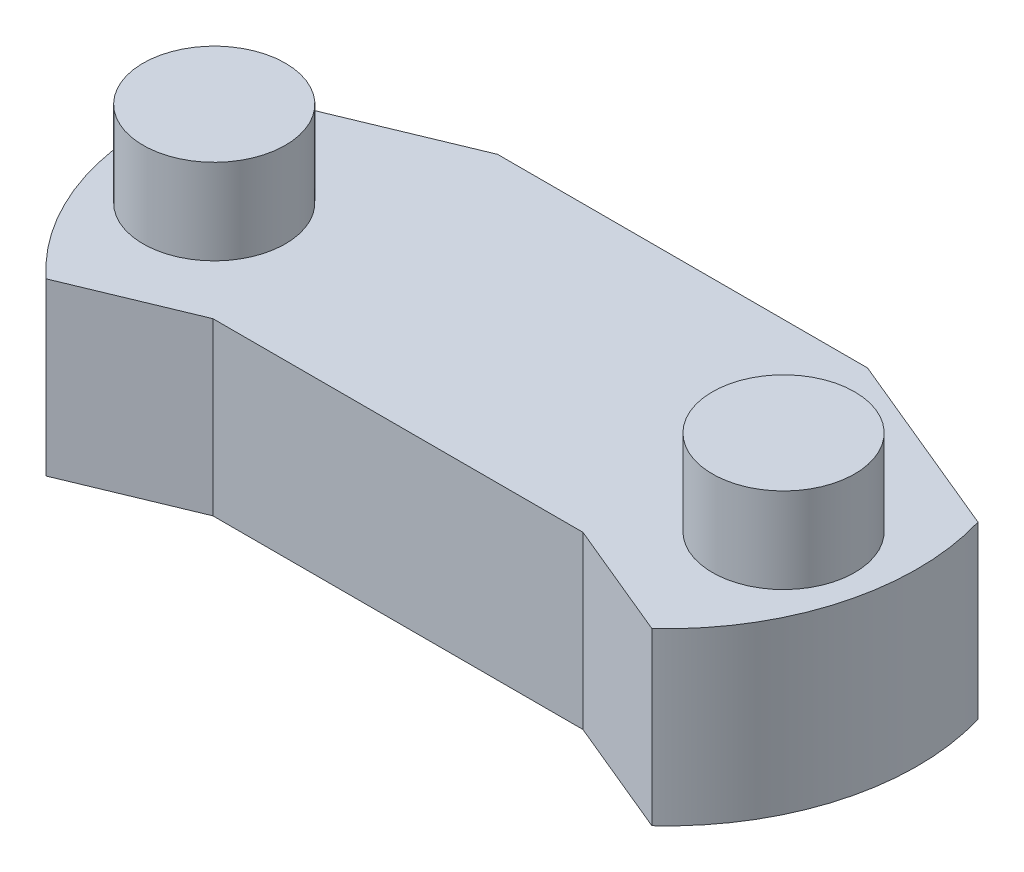
SolidWorks part; units mm, degrees
ref_plane "Front Plane" through (0, 0, 0) normal (0, 0, 1) x (1, 0, 0)
ref_plane "Top Plane" through (0, 0, 0) normal (0, 1, 0) x (1, 0, 0)
ref_plane "Right Plane" through (0, 0, 0) normal (1, 0, 0) x (0, 0, -1)
sketch "Sketch2" plane through (0, 0, 0) normal (0, 1, 0) x (1, 0, 0)
  line L0 (-21.487, 36.3493) -> (-21.487, -13.6507)
  line L3 (-21.487, -13.6507) -> (43.513, -13.6507)
  line L5 (-21.487, 36.3493) -> (-56.487, 21.8321)
  line L6 (-21.487, -13.6507) -> (-56.487, -28.1679)
  line L7 (-56.487, 21.8321) -> (-56.487, -28.1679)
  line L13 (43.513, -13.6507) -> (43.513, 36.3493)
  line L14 (-56.487, -28.1679) -> (-21.487, 36.3493)
  line L15 (-56.487, 21.8321) -> (-21.487, -13.6507)
  line L16 (-21.487, -13.6507) -> (-21.487, 36.3493)
  line L18 (-21.487, 36.3493) -> (43.513, 36.3493)
  line L19 (11.013, -53.9884) -> (11.013, 63.9884)
  line L20 (78.513, 21.8321) -> (43.513, -13.6507)
  line L21 (78.513, -28.1679) -> (43.513, 36.3493)
  line L22 (78.513, 21.8321) -> (78.513, -28.1679)
  line L23 (43.513, -13.6507) -> (78.513, -28.1679)
  line L24 (43.513, 36.3493) -> (78.513, 21.8321)
  line L25 (43.513, 36.3493) -> (43.513, -13.6507)
  circle A3 centre (-38.987, 4.0907) radius 12.5
  circle A4 centre (61.013, 4.0907) radius 12.5
  point P4 (11.013, 36.3493)
  point P9 (11.013, -13.6507)
  point P18 (11.013, 5)
  dimension "D4" = 35
  dimension "D3" = 50
  dimension "D1" = 25
  dimension "D2" = 50
extrude "Boss-Extrude1" add sketch "Sketch2" along normal blind 30 contours A3 L14 L5 L15 | A3 L15 L7 L14 | A3 L14 L6 L15 | A3 L15 L0 L14 | L3 L19 L18 L0 | L20 A4 L21 L13 | L21 A4 L20 L24 | L20 A4 L21 L22 | L21 A4 L20 L23 | L19 L3 L13 L18
fillet "Fillet1" radius 3 4 edges at (-56.487, 15, -21.8321) (-56.487, 15, 28.1679) (78.513, 15, -21.8321) (78.513, 15, 28.1679)
sketch "Sketch3" plane through (0, 0, 0) normal (0, -1, 0) x (-1, 0, 0)
  circle A1 centre (38.987, 4.0907) radius 12.5
  circle A2 centre (-61.013, 4.0907) radius 12.5
  dimension "D1" = 25
  dimension "D2" = 25
extrude "Boss-Extrude2" add sketch "Sketch3" against normal blind 45
sketch "Sketch4" plane through (0, 30, 0) normal (0, 1, 0) x (1, 0, 0)
  line L2 (-21.487, -13.6507) -> (-52.3376, -26.4468) construction
  line L7 (11.013, 36.3493) -> (11.013, -13.6507)
  line L8 (74.3636, -26.4468) -> (64.2102, -22.2354)
  line L9 (-52.3376, -26.4468) -> (-21.487, -13.6507)
  line L10 (-56.487, 19.8286) -> (-56.487, -23.6757)
  line L11 (-52.3376, -26.4468) -> (-42.1841, -22.2354)
  line L12 (-56.487, 19.8286) -> (-56.487, -23.6757)
  line L13 (78.513, 19.8286) -> (78.513, -23.6757)
  arc A0 (-54.6364, 22.5997) -> (-42.1841, -22.2354) centre (-12.5033, 10.1548) ccw
  arc A8 (78.513, -23.6757) -> (74.3636, -26.4468) centre (75.513, -23.6757) cw
  arc A9 (76.6624, 22.5997) -> (78.513, 19.8286) centre (75.513, 19.8286) cw
  arc A10 (-56.487, -23.6757) -> (-52.3376, -26.4468) centre (-53.487, -23.6757) ccw
  arc A11 (-54.6364, 22.5997) -> (-56.487, 19.8286) centre (-53.487, 19.8286) ccw
  arc A12 (-56.487, -23.6757) -> (-52.3376, -26.4468) centre (-53.487, -23.6757) ccw
  arc A13 (-54.6364, 22.5997) -> (-56.487, 19.8286) centre (-53.487, 19.8286) ccw
  arc A14 (76.6624, 22.5997) -> (64.2102, -22.2354) centre (34.5293, 10.1548) cw
  arc M9 (-54.6364, 22.5997) -> (-56.487, 19.8286) centre (-53.487, 19.8286) ccw
  line M10 (-56.487, 19.8286) -> (-56.487, -23.6757)
  arc M11 (-56.487, -23.6757) -> (-52.3376, -26.4468) centre (-53.487, -23.6757) ccw
  line M12 (-52.3376, -26.4468) -> (-21.487, -13.6507)
  line M14 (43.513, -13.6507) -> (74.3636, -26.4468)
  arc M15 (74.3636, -26.4468) -> (78.513, -23.6757) centre (75.513, -23.6757) ccw
  line M16 (78.513, -23.6757) -> (78.513, 19.8286)
  arc M17 (78.513, 19.8286) -> (76.6624, 22.5997) centre (75.513, 19.8286) ccw
  dimension "D1" = 0
extrude "Cut-Extrude1" cut sketch "Sketch4" against normal through all contours A0 M9 M10 M11 M12 | A14 M17 M14 M15 M16
